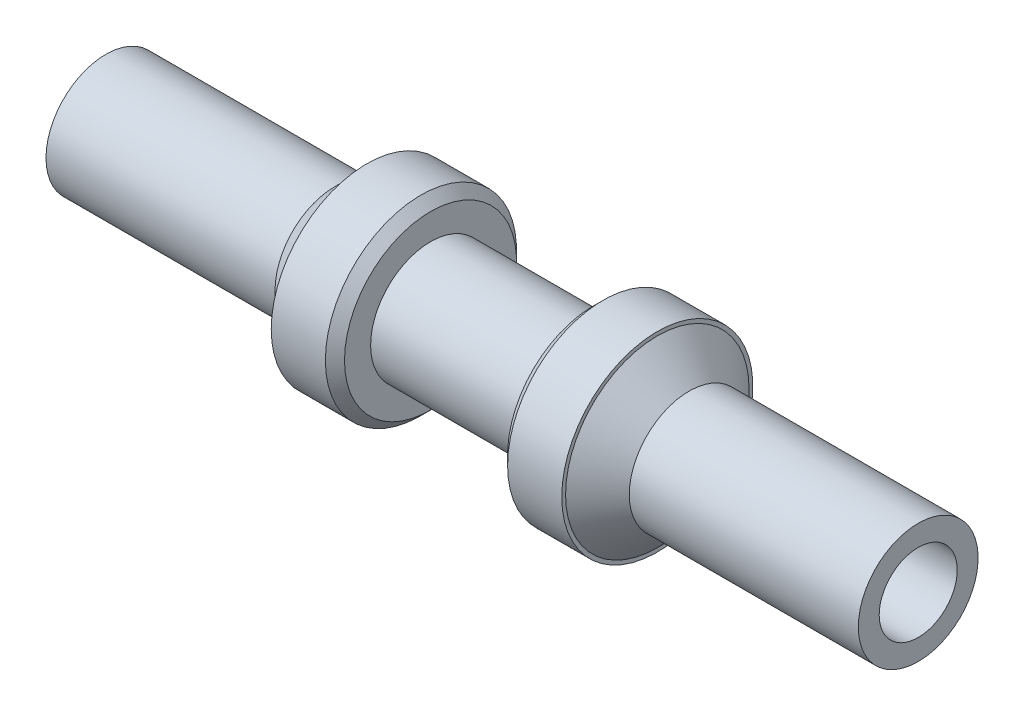
SolidWorks part; units mm, degrees
ref_plane "Front Plane" through (0, 0, 0) normal (0, 0, 1) x (1, 0, 0)
ref_plane "Top Plane" through (0, 0, 0) normal (0, 1, 0) x (1, 0, 0)
ref_plane "Right Plane" through (0, 0, 0) normal (1, 0, 0) x (0, 0, -1)
sketch "Sketch1" plane through (0, 0, 0) normal (0, 0, 1) x (1, 0, 0)
  line L0 (0, 0) -> (23682.6092, 0) construction
  line L1 (0, 3.1115) -> (0, 4.7752)
  line L2 (0, 4.7752) -> (20.8026, 4.7752)
  line L3 (20.8026, 4.7752) -> (20.8026, 7.62)
  line L4 (20.8026, 7.62) -> (25.8826, 7.62)
  line L5 (25.8826, 7.62) -> (25.8826, 4.7752)
  line L6 (25.8826, 4.7752) -> (38.8874, 4.7752)
  line L7 (38.8874, 4.7752) -> (38.8874, 7.62)
  line L8 (38.8874, 7.62) -> (43.9674, 7.62)
  line L9 (43.9674, 7.62) -> (43.9674, 4.7752)
  line L10 (43.9674, 4.7752) -> (64.77, 4.7752)
  line L11 (64.77, 4.7752) -> (64.77, 3.1115)
  line L12 (64.77, 3.1115) -> (0, 3.1115)
  dimension "D1" = 13.0048
  dimension "D2" = 64.77
  dimension "D3" = 4.7752
  dimension "D4" = 5.08
  dimension "D5" = 7.62
  dimension "D6" = 3.1115
revolve "Revolve1" add sketch "Sketch1" angle 360 about L0
chamfer "Chamfer1" distance 0.762 angle 45 2 edges at (38.8874, 0, 7.62) (25.8826, 0, 7.62)
chamfer "Chamfer2" distance 2.54 angle 45 2 edges at (20.8026, 0, 4.7752) (43.9674, 0, 4.7752)
